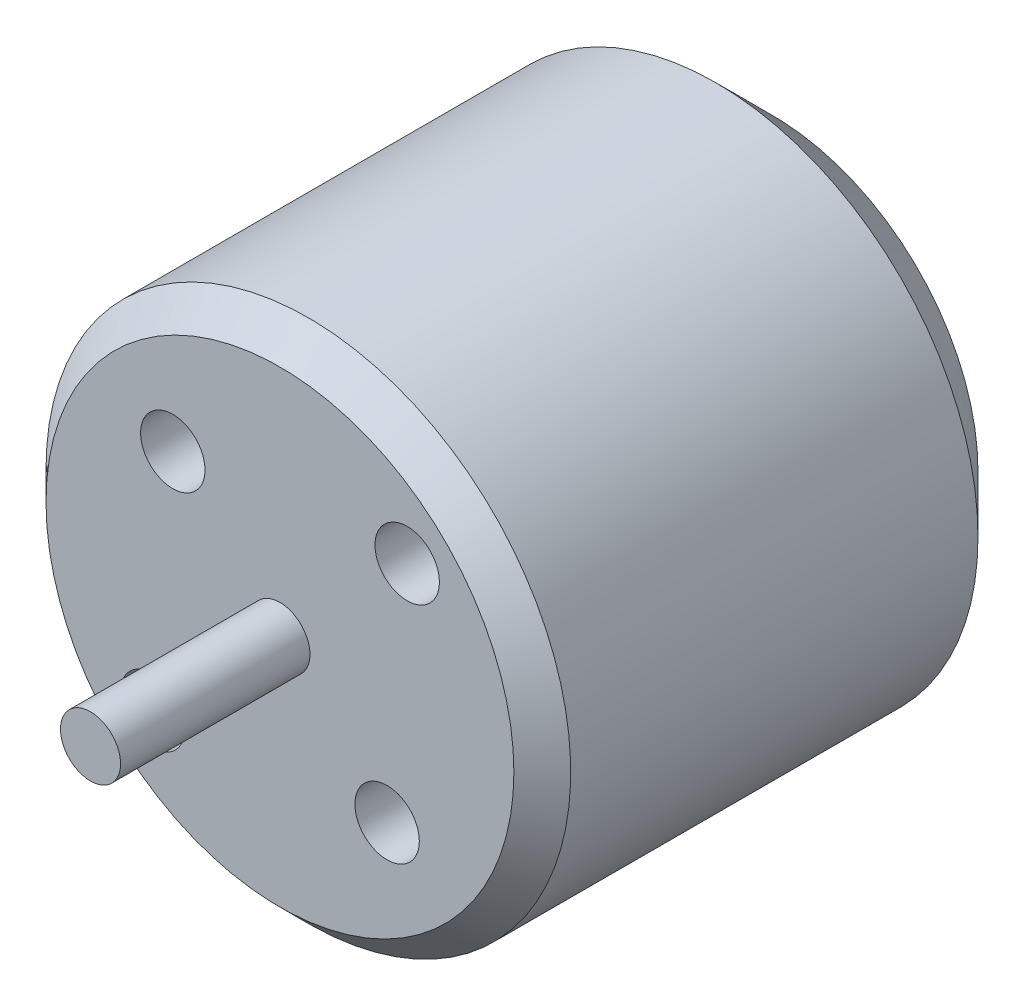
SolidWorks part; units mm, degrees
ref_plane "Front Plane" through (0, 0, 0) normal (0, 0, 1) x (1, 0, 0)
ref_plane "Top Plane" through (0, 0, 0) normal (0, 1, 0) x (1, 0, 0)
ref_plane "Right Plane" through (0, 0, 0) normal (1, 0, 0) x (0, 0, -1)
sketch "Sketch1" plane through (0, 0, 0) normal (0, 0, 1) x (1, 0, 0)
  circle A0 centre (0, 0) radius 13.85
  dimension "D1" = 27.7
extrude "Boss-Extrude1" add sketch "Sketch1" along normal blind 26
chamfer "Chamfer1" distance 1.5 angle 45 1 edges at (13.85, 0, 26)
chamfer "Chamfer2" distance 3 angle 45 1 edges at (13.85, 0, 0)
sketch "Sketch2" plane through (0, 0, 0) normal (0, 0, -1) x (-1, 0, 0)
  circle A0 centre (0, 0) radius 4.5
  dimension "D1" = 9
extrude "Boss-Extrude2" add sketch "Sketch2" along normal blind 4
sketch "Sketch3" plane through (0, 0, 26) normal (0, 0, 1) x (1, 0, 0)
  circle A0 centre (0, 0) radius 1.585
  dimension "D1" = 3.17
extrude "Boss-Extrude3" add sketch "Sketch3" along normal blind 10
sketch "Sketch4" plane through (0, 0, 26) normal (0, 0, 1) x (1, 0, 0)
  line L0 (5.6569, -5.6569) -> (-5.6569, 5.6569) construction
  line L1 (-6.7175, -6.7175) -> (6.7175, 6.7175) construction
  line L2 (0, 0) -> (0, 12.35) construction
  circle A0 centre (0, 0) radius 12.35 construction
  point P5 (0, 0)
  point P9 (0, 0)
  dimension "D1" = 19
  dimension "D2" = 16
  dimension "D3" = 45
hole_wizard "M3 Clearance Hole1" positions "Sketch5" profile "Sketch6" hole size "M3" standard "ANSI Metric"
sketch "Sketch5" plane through (0, 0, 26) normal (0, 0, 1) x (1, 0, 0)
  point P0 (-5.6569, 5.6569)
  point P3 (6.7175, 6.7175)
  point P6 (5.6569, -5.6569)
  point P9 (-6.7175, -6.7175)
sketch "Sketch6" plane through (-5.6569, 5.6569, 26) normal (1, 0, 0) x (0, -1, 0)
  line L0 (0, 0) -> (0, 11.0215)
  line L1 (0, 11.0215) -> (1.7, 10)
  line L2 (1.7, 10) -> (1.7, 0)
  line L5 (1.7, 0) -> (0, 0)
  line L10 (0, 11.0215) -> (-1.7, 10) construction
  line L11 (0, -6.35) -> (0, 107.95) construction
  dimension "Hole Dia." = 3.4
  dimension "Hole Depth" = 10
  dimension "Drill Angle" = 118
sketch "Sketch7" plane through (0, 0, 0) normal (0, 0, -1) x (-1, 0, 0)
  line L0 (0, 6) -> (0, 0) construction
  line L1 (0, 0) -> (-5.1962, -3) construction
  line L2 (0, 0) -> (5.1962, -3) construction
  circle A0 centre (0, 0) radius 6
  point P3 (0, 6)
  dimension "D1" = 12
  dimension "D2" = 120
  dimension "D3" = 120
hole_wizard "M2 Clearance Hole1" positions "Sketch8" profile "Sketch9" hole size "M2" standard "ANSI Metric"
sketch "Sketch8" plane through (0, 0, 0) normal (0, 0, -1) x (-1, 0, 0)
  point P0 (0, 6)
  point P3 (5.1962, -3)
  point P6 (-5.1962, -3)
sketch "Sketch9" plane through (0, 6, 0) normal (1, 0, 0) x (0, 1, 0)
  line L0 (0, 0) -> (0, 10.721)
  line L1 (0, 10.721) -> (1.2, 10)
  line L2 (1.2, 10) -> (1.2, 0)
  line L5 (1.2, 0) -> (0, 0)
  line L10 (0, 10.721) -> (-1.2, 10) construction
  line L11 (0, -6.35) -> (0, 107.95) construction
  dimension "Hole Dia." = 2.4
  dimension "Hole Depth" = 10
  dimension "Drill Angle" = 118
